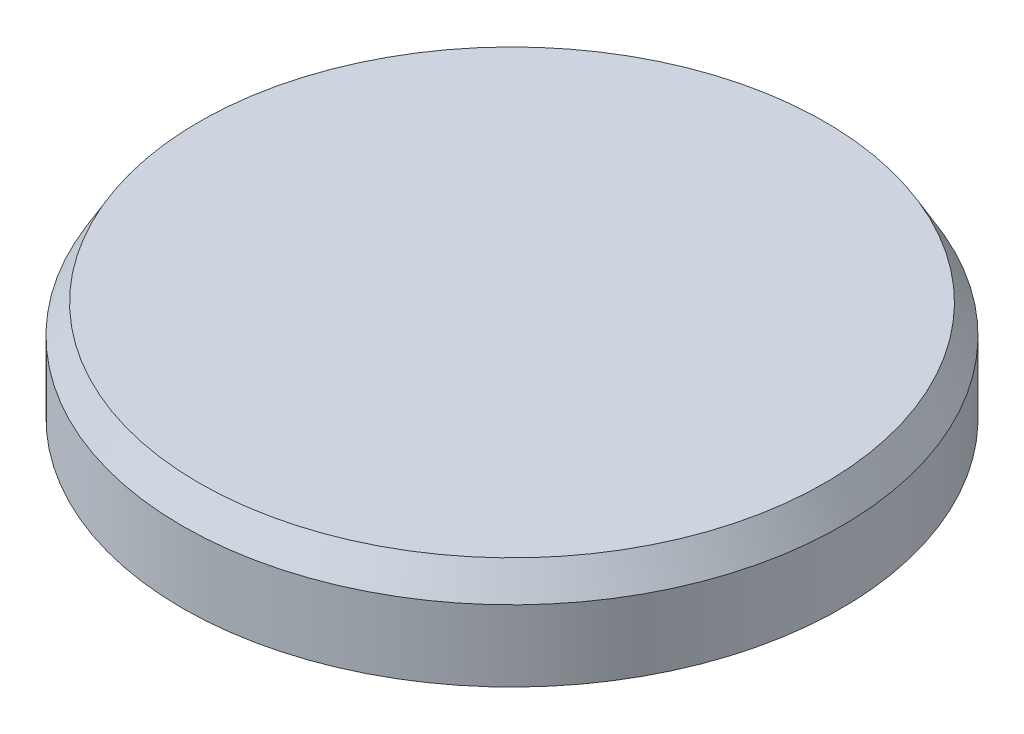
SolidWorks part; units mm, degrees
ref_plane "前视基准面" through (0, 0, 0) normal (0, 0, 1) x (1, 0, 0)
ref_plane "上视基准面" through (0, 0, 0) normal (0, 1, 0) x (1, 0, 0)
ref_plane "右视基准面" through (0, 0, 0) normal (1, 0, 0) x (0, 0, -1)
sketch "草图1" plane through (0, 0, 0) normal (0, 1, 0) x (1, 0, 0)
  circle A0 centre (0, 0) radius 15.75
  circle A1 centre (0, 0) radius 19.75
  dimension "D1" = 31.5
  dimension "D2" = 4
extrude "凸台-拉伸1" add sketch "草图1" along normal blind 4
sketch "草图2" plane through (0, 4, 0) normal (0, 1, 0) x (1, 0, 0)
  circle A0 centre (0, 0) radius 19.75
  circle A1 centre (0, 0) radius 19.75 construction
extrude "凸台-拉伸2" add sketch "草图2" along normal blind 2
sketch "草图3" plane through (0, 4, 0) normal (0, -1, 0) x (1, 0, 0)
  line L0 (0, 0) -> (16.5, 0) construction
  circle A3 centre (0, 0) radius 16.5
  dimension "D1" = 33
extrude "切除-拉伸1" cut sketch "草图3" along normal up to surface (4 mm away) up to face at (0, 0, 19.75)
sketch "草图4" plane through (0, 4, 0) normal (0, -1, 0) x (1, 0, 0)
  line L0 (15.9378, 4.2705) -> (15.2133, 4.0764) construction
  line L1 (0, 0) -> (19.75, 0) construction
  line L2 (15.9378, -4.2705) -> (15.2133, -4.0764) construction
  arc A1 (15.7272, -4.9904) -> (15.2133, -4.0764) centre (15.9378, -4.2705) cw
  circle A2 centre (0, 0) radius 15.75 construction
  circle A3 centre (0, 0) radius 16.5 construction
  circle A4 centre (0, 0) radius 19.75 construction
  arc A5 (15.2133, 4.0764) -> (15.2133, -4.0764) centre (0, 0) cw
  arc A6 (15.7272, 4.9904) -> (15.2133, 4.0764) centre (15.9378, 4.2705) ccw
  circle A7 centre (0, 0) radius 16.5 construction
  arc A8 (15.7272, -4.9904) -> (15.7272, 4.9904) centre (0, 0) ccw
  point P11 (0, 0)
  point P14 (0, 0)
  dimension "D1" = 31.5
  dimension "D2" = 15
extrude "凸台-拉伸3" add sketch "草图4" along normal up to surface (4 mm away) up to face at (0, 0, 16.5)
pattern_circular "阵列(圆周)1" count 3 over 360 about axis through (0, 0, 0) along (0, 1, 0) of "凸台-拉伸3"
chamfer "倒角1" distance 1 angle 60 1 edges at (0, 6, 19.75)
